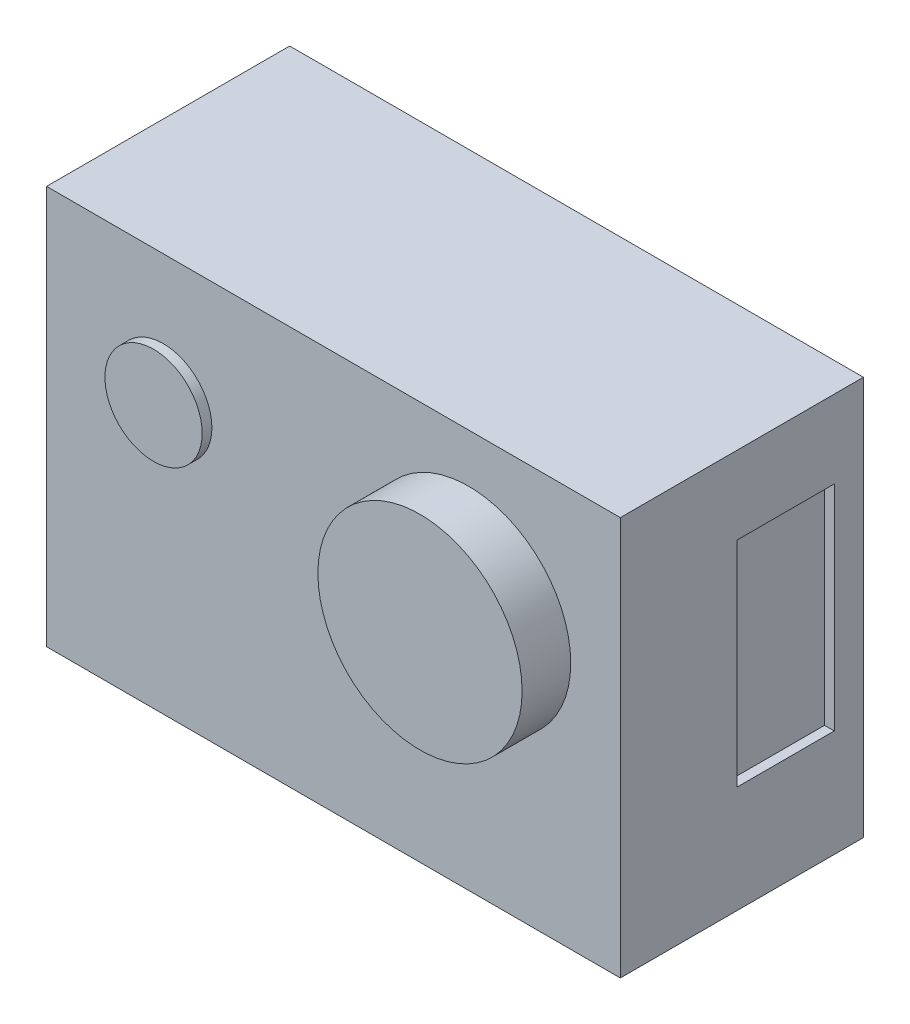
SolidWorks part; units mm, degrees
ref_plane "Спереди" through (0, 0, 0) normal (0, 0, 1) x (1, 0, 0)
ref_plane "Сверху" through (0, 0, 0) normal (0, 1, 0) x (1, 0, 0)
ref_plane "Справа" through (0, 0, 0) normal (1, 0, 0) x (0, 0, -1)
sketch "Эскиз1" plane through (0, 0, 0) normal (0, 0, 1) x (1, 0, 0)
  line L1 (-29.5, 20.5) -> (29.5, 20.5)
  line L2 (-29.5, 20.5) -> (-29.5, -20.5)
  line L3 (-29.5, -20.5) -> (29.5, -20.5)
  line L4 (29.5, 20.5) -> (29.5, -20.5)
  line L5 (-29.5, 20.5) -> (29.5, -20.5) construction
  line L6 (-29.5, -20.5) -> (29.5, 20.5) construction
  point P0 (0, 0)
  dimension "D1" = 59
  dimension "D2" = 41
extrude "Бобышка-Вытянуть1" add sketch "Эскиз1" along normal blind 25 contours L1 L4 L3 L2
sketch "Эскиз2" plane through (0, 0, 25) normal (0, 0, 1) x (1, 0, 0)
  line L4 (-29.5, 20.5) -> (-29.5, -20.5)
  line L5 (-29.5, -20.5) -> (29.5, -20.5)
  line L6 (29.5, -20.5) -> (29.5, 20.5)
  line L7 (29.5, 20.5) -> (-29.5, 20.5)
  line L10 (29.5, -20.5) -> (29.5, 20.5)
  line L11 (29.5, 20.5) -> (-29.5, 20.5)
  circle A0 centre (13.9, 5) radius 10.5
  point P4 (13.9, 15.5)
  point P8 (3.4, 5)
  dimension "D2" = 21
  dimension "D3" = 5
  dimension "D4" = 26.1
  dimension "D1" = 0
extrude "Бобышка-Вытянуть2" add sketch "Эскиз2" along normal blind 5 contours A0
sketch "Эскиз5" plane through (0, 0, 25) normal (0, 0, 1) x (1, 0, 0)
  line L1 (-29.5, 20.5) -> (-29.5, -20.5) construction
  line L2 (-29.5, 20.5) -> (29.5, 20.5) construction
  circle A0 centre (-17.5, 7.5) radius 5
  point P2 (-17.5, 2.5)
  dimension "D1" = 10
  dimension "D2" = 13
  dimension "D3" = 12
extrude "Бобышка-Вытянуть3" add sketch "Эскиз5" along normal blind 1
sketch "Эскиз6" plane through (29.5, 0, 0) normal (1, 0, 0) x (0, 0, -1)
  line L0 (0, 0) -> (-25, 0) construction
  line L1 (-13, 12.5) -> (-3, 12.5)
  line L2 (-13, 12.5) -> (-13, -9.5)
  line L3 (-13, -9.5) -> (-3, -9.5)
  line L4 (-3, 12.5) -> (-3, -9.5)
  line L5 (-25, 20.5) -> (-25, -20.5) construction
  line L6 (-25, -20.5) -> (0, -20.5) construction
  line L7 (-25, 20.5) -> (0, 20.5) construction
  line L8 (-25, 15.5) -> (-25, -5.5) construction
  dimension "D1" = 11
  dimension "D2" = 8
  dimension "D3" = 10
  dimension "D4" = 12
extrude "Вырез-Вытянуть1" cut sketch "Эскиз6" against normal blind 1 contours L1 L4 L3 L2
